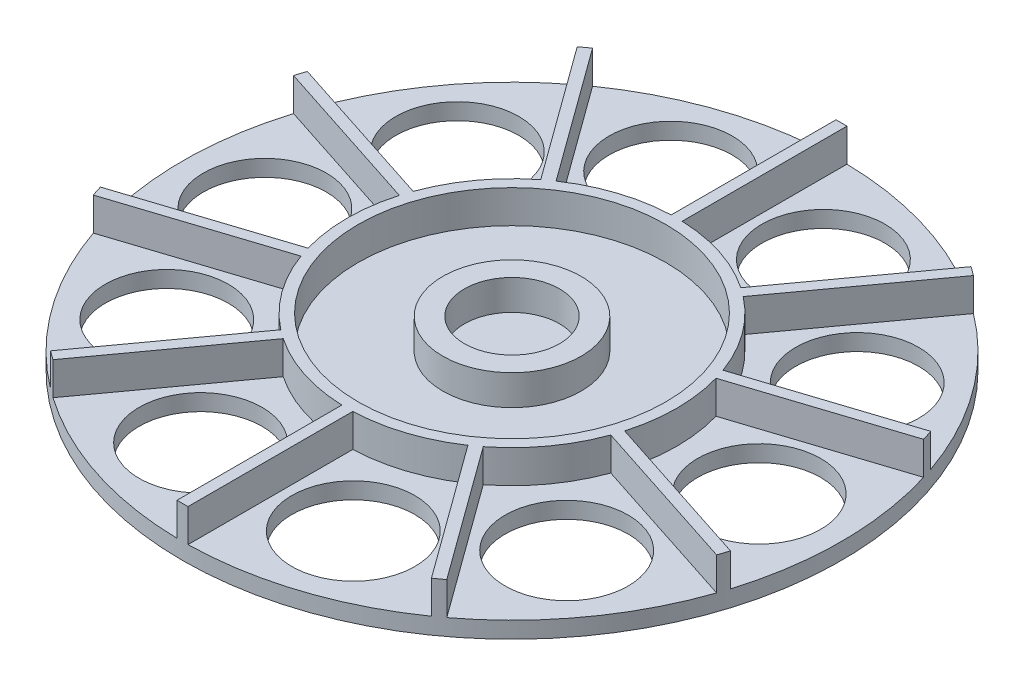
SolidWorks part; units mm, degrees
ref_plane "Front Plane" through (0, 0, 0) normal (0, 0, 1) x (1, 0, 0)
ref_plane "Top Plane" through (0, 0, 0) normal (0, 1, 0) x (1, 0, 0)
ref_plane "Right Plane" through (0, 0, 0) normal (1, 0, 0) x (0, 0, -1)
sketch "Sketch1" plane through (0, 0, 0) normal (0, 1, 0) x (1, 0, 0)
  circle A0 centre (-57.15, 0) radius 15.494 construction
  circle A1 centre (-46.2353, 33.5919) radius 15.494 construction
  circle A2 centre (-17.6603, 54.3529) radius 15.494 construction
  circle A3 centre (17.6603, 54.3529) radius 15.494 construction
  circle A4 centre (46.2353, 33.5919) radius 15.494 construction
  circle A5 centre (57.15, 0) radius 15.494 construction
  circle A6 centre (46.2353, -33.5919) radius 15.494 construction
  circle A7 centre (17.6603, -54.3529) radius 15.494 construction
  circle A8 centre (-17.6603, -54.3529) radius 15.494 construction
  circle A9 centre (0, 0) radius 76.2
  circle A10 centre (-57.15, 0) radius 14.224
  circle A11 centre (-46.2353, 33.5919) radius 14.224
  circle A12 centre (-17.6603, 54.3529) radius 14.224
  circle A13 centre (17.6603, 54.3529) radius 14.224
  circle A14 centre (46.2353, 33.5919) radius 14.224
  circle A15 centre (57.15, 0) radius 14.224
  circle A16 centre (46.2353, -33.5919) radius 14.224
  circle A17 centre (17.6603, -54.3529) radius 14.224
  circle A18 centre (-17.6603, -54.3529) radius 14.224
  circle A19 centre (-46.2353, -33.5919) radius 15.494 construction
  circle A20 centre (-46.2353, -33.5919) radius 14.224
  point P2 (0, 0)
  point P23 (0, 0)
  dimension "D1" = 30.988
  dimension "D2" = 57.15
  dimension "D3" = 10
  dimension "D4" = 28.448
  dimension "D5" = 152.4
extrude "Boss-Extrude1" add sketch "Sketch1" along normal blind 3.81
sketch "Sketch3" plane through (0, 3.81, 0) normal (0, 1, 0) x (1, 0, 0)
  circle A0 centre (0, 0) radius 35.56
  circle A1 centre (0, 0) radius 38.1
  dimension "D1" = 2.54
  dimension "D2" = 76.2
extrude "Boss-Extrude3" add sketch "Sketch3" along normal blind 7.62
sketch "Sketch2" plane through (0, 3.81, 0) normal (0, 1, 0) x (1, 0, 0)
  line L0 (0, 0) -> (-106.3551, -34.5569) construction
  line L1 (0, 0) -> (-57.15, 0) construction
  line L32 (-72.8529, -22.336) -> (-36.6076, -10.5592)
  line L33 (-72.068, -24.7517) -> (-35.8227, -12.9748)
  line L34 (-72.068, 24.7517) -> (-35.8227, 12.9748)
  line L35 (-72.8529, 22.336) -> (-36.6076, 10.5592)
  line L36 (-43.7556, 62.385) -> (-21.3547, 31.5529)
  line L37 (-45.8105, 60.892) -> (-23.4096, 30.0599)
  line L38 (1.27, 76.1894) -> (1.27, 38.0788)
  line L39 (-1.27, 76.1894) -> (-1.27, 38.0788)
  line L40 (45.8105, 60.892) -> (23.4096, 30.0599)
  line L41 (43.7556, 62.385) -> (21.3547, 31.5529)
  line L42 (72.8529, 22.336) -> (36.6076, 10.5592)
  line L43 (72.068, 24.7517) -> (35.8227, 12.9748)
  line L44 (72.068, -24.7517) -> (35.8227, -12.9748)
  line L45 (72.8529, -22.336) -> (36.6076, -10.5592)
  line L46 (43.7556, -62.385) -> (21.3547, -31.5529)
  line L47 (45.8105, -60.892) -> (23.4096, -30.0599)
  line L48 (-1.27, -76.1894) -> (-1.27, -38.0788)
  line L49 (1.27, -76.1894) -> (1.27, -38.0788)
  line L50 (-45.8105, -60.892) -> (-23.4096, -30.0599)
  line L51 (-43.7556, -62.385) -> (-21.3547, -31.5529)
  arc A0 (-36.6076, 10.5592) -> (-35.8227, 12.9748) centre (0, 0) cw
  arc A22 (-72.8529, 22.336) -> (-72.068, 24.7517) centre (0, 0) cw
  circle A23 centre (0, 0) radius 76.2 construction
  circle A24 centre (0, 0) radius 38.1 construction
  arc A25 (-35.8227, -12.9748) -> (-36.6076, -10.5592) centre (0, 0) cw
  arc A26 (-72.068, -24.7517) -> (-72.8529, -22.336) centre (0, 0) cw
  arc A27 (-23.4096, 30.0599) -> (-21.3547, 31.5529) centre (0, 0) cw
  arc A28 (-45.8105, 60.892) -> (-43.7556, 62.385) centre (0, 0) cw
  arc A29 (-1.27, 38.0788) -> (1.27, 38.0788) centre (0, 0) cw
  arc A30 (-1.27, 76.1894) -> (1.27, 76.1894) centre (0, 0) cw
  arc A31 (21.3547, 31.5529) -> (23.4096, 30.0599) centre (0, 0) cw
  arc A32 (43.7556, 62.385) -> (45.8105, 60.892) centre (0, 0) cw
  arc A33 (35.8227, 12.9748) -> (36.6076, 10.5592) centre (0, 0) cw
  arc A34 (72.068, 24.7517) -> (72.8529, 22.336) centre (0, 0) cw
  arc A35 (36.6076, -10.5592) -> (35.8227, -12.9748) centre (0, 0) cw
  arc A36 (72.8529, -22.336) -> (72.068, -24.7517) centre (0, 0) cw
  arc A37 (23.4096, -30.0599) -> (21.3547, -31.5529) centre (0, 0) cw
  arc A38 (45.8105, -60.892) -> (43.7556, -62.385) centre (0, 0) cw
  arc A39 (1.27, -38.0788) -> (-1.27, -38.0788) centre (0, 0) cw
  arc A40 (1.27, -76.1894) -> (-1.27, -76.1894) centre (0, 0) cw
  arc A41 (-21.3547, -31.5529) -> (-23.4096, -30.0599) centre (0, 0) cw
  arc A42 (-43.7556, -62.385) -> (-45.8105, -60.892) centre (0, 0) cw
  point P52 (0, 0)
  dimension "D2" = 2.54
  dimension "D1" = 18
  dimension "D3" = 10
extrude "Boss-Extrude4" add sketch "Sketch2" along normal up to surface (7.62 mm away) up to face at (0, 11.43, 38.1)
sketch "Sketch4" plane through (0, 3.81, 0) normal (0, 1, 0) x (1, 0, 0)
  circle A0 centre (0, 0) radius 11
  circle A1 centre (0, 0) radius 16
  dimension "D1" = 5
  dimension "D2" = 22
extrude "Boss-Extrude5" add sketch "Sketch4" along normal blind 7
